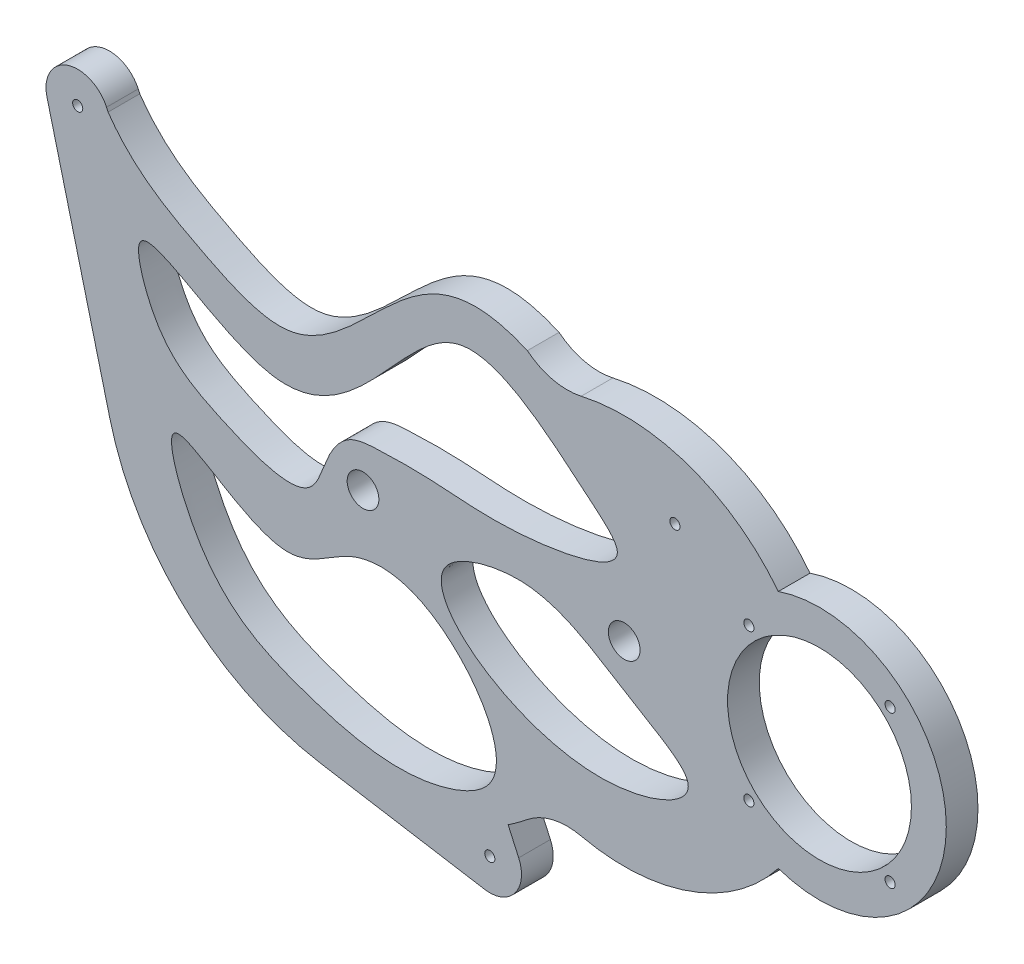
SolidWorks part; units mm, degrees
ref_plane "Front Plane" through (0, 0, 0) normal (0, 0, 1) x (1, 0, 0)
ref_plane "Top Plane" through (0, 0, 0) normal (0, 1, 0) x (1, 0, 0)
ref_plane "Right Plane" through (0, 0, 0) normal (1, 0, 0) x (0, 0, -1)
sketch "Sketch2" plane through (0, 0, 0) normal (0, 0, 1) x (1, 0, 0)
  line L0 (-49.7403, 0) -> (-8.5403, 0) construction
  line L1 (-8.5403, 0) -> (22.2597, 0) construction
  line L2 (22.2597, 0) -> (62.8428, 0) construction
  line L3 (-90.1933, 32.0796) -> (-89.9454, 31.5376)
  line L4 (-97.1991, 19.399) -> (-89.6649, -10.1721)
  line L5 (-97.1991, 19.399) -> (-99.5855, 28.7655)
  line L6 (-30.5563, -44.933) -> (-56.4637, -40.6477)
  line L7 (-25.1846, -37.9395) -> (-26.8505, -34.2563)
  line L9 (11.1236, -11.9713) -> (33.3957, -11.9713) construction
  line L10 (11.1236, -11.9713) -> (11.1236, 11.9713) construction
  line L11 (11.1236, 11.9713) -> (33.3957, 11.9713) construction
  line L12 (33.3957, -11.9713) -> (33.3957, 11.9713) construction
  line L13 (11.1236, -11.9713) -> (33.3957, 11.9713) construction
  line L14 (11.1236, 11.9713) -> (33.3957, -11.9713) construction
  arc A1 (-15.3257, -30.0433) -> (15.7662, -18.9165) centre (-8.5403, 0) ccw
  arc A3 (-15.3257, -30.0433) -> (-23.82, -32.0246) centre (-17.5287, -39.7976) ccw
  arc A4 (-15.3257, 30.0433) -> (-23.82, 32.0246) centre (-17.5287, 39.7976) cw
  circle A5 centre (22.2597, 0) radius 14.5
  arc A6 (15.7662, -18.9165) -> (15.7662, 18.9165) centre (22.2597, 0) ccw
  arc A7 (15.7662, 18.9165) -> (-15.3257, 30.0433) centre (-8.5403, 0) ccw
  circle A8 centre (-49.7403, 0) radius 2.5
  circle A9 centre (-8.5403, 0) radius 2.5
  arc A10 (-30.5563, -44.933) -> (-25.1846, -37.9395) centre (-29.7403, -40) ccw
  arc A11 (-90.1933, 32.0796) -> (-99.5855, 28.7655) centre (-94.7403, 30) ccw
  arc A12 (-89.6649, -10.1721) -> (-56.4637, -40.6477) centre (-49.7403, 0) ccw
  arc A13 (-26.8505, -34.2563) -> (-23.82, -32.0246) centre (-49.7403, 0) ccw
  circle A14 centre (-94.7403, 30) radius 0.8
  circle A15 centre (-29.7403, -40) radius 0.8
  circle A16 centre (-0.5403, 20) radius 0.8
  circle A17 centre (33.3957, 11.9713) radius 0.8
  circle A18 centre (11.1236, 11.9713) radius 0.8
  circle A19 centre (11.1236, -11.9713) radius 0.8
  circle A20 centre (33.3957, -11.9713) radius 0.8
  spline S0 degree 3 poles (-39.2229, 38.3177) (-54.9055, -5.8181) (-88.7377, 24.2535) (-82.168, 3.7127) (-72.9101, -1.436) (-57.6184, -7.4663) (-55.624, 2.1473) (-52.0058, 6.5153) (-46.7468, 6.7602) (-36.8994, 7.0155) (-27.0746, 5.0384) (-5.7221, 9.6224) (-19.1219, 20.9552) (-39.2229, 38.3177) (-54.9055, -5.8181) (-88.7377, 24.2535) knots -0.362538 -0.329997 -0.196661 0 0.124196 0.177433 0.253963 0.332107 0.369145 0.395899 0.421744 0.453106 0.559647 0.637462 0.670003 0.803339 1 1.124196 1.177433 1.253963 only from (-64.1468, 8.5429) to (-64.1468, 8.5429)
  spline S1 degree 3 poles (-74.7601, -25.5673) (-84.5087, 1.4119) (-62.9178, -19.5533) (-52.2802, -8.6864) (-36.961, -8.725) (-23.0127, -28.4606) (-42.0384, -36.9973) (-59.0966, -32.7658) (-74.7601, -25.5673) (-84.5087, 1.4119) (-62.9178, -19.5533) knots -0.437271 -0.263713 -0.110111 0 0.152444 0.236085 0.315357 0.495919 0.562729 0.736287 0.889889 1 1.152444 1.236085 1.315357 only from (-79.5553, -7.1228) to (-79.5553, -7.1228)
  spline S2 degree 3 poles (-11.5115, -5.5592) (-21.3225, 2.5431) (-46.6957, -5.3006) (-18.8729, -26.4193) (6.8712, -15.4824) (-11.5115, -5.5592) (-21.3225, 2.5431) (-46.6957, -5.3006) knots -0.541669 -0.369791 -0.256687 0 0.116637 0.458331 0.630209 0.743313 1 1.116637 1.458331 1.630209 only from (-26.8505, 0) to (-26.8505, 0)
  spline S3 degree 3 poles (-89.9454, 31.5376) (-85.9622, 25.8016) (-77.2412, 20.8489) (-60.7719, 12.8688) (-45.0949, 27.5523) (-35.7111, 37.2489) (-23.82, 32.0246) knots 0 0 0 0 0.248037 0.436902 0.633306 1 1 1 1
  dimension "D3" = 10
  dimension "D4" = 29
  dimension "D5" = 10
  dimension "D6" = 10
  dimension "D12" = 30.8
  dimension "D13" = 1.6
  dimension "D14" = 1.6
  dimension "D15" = 1.6
  dimension "D19" = 1.6
  dimension "D1" = 41.2
  dimension "D2" = 30.8
  dimension "D7" = 45
  dimension "D8" = 30
  dimension "D9" = 40
  dimension "D10" = 20
  dimension "D16" = 20
  dimension "D17" = 8
  dimension "D18" = 32.7
extrude "Boss-Extrude2" add sketch "Sketch2" along normal blind 5
